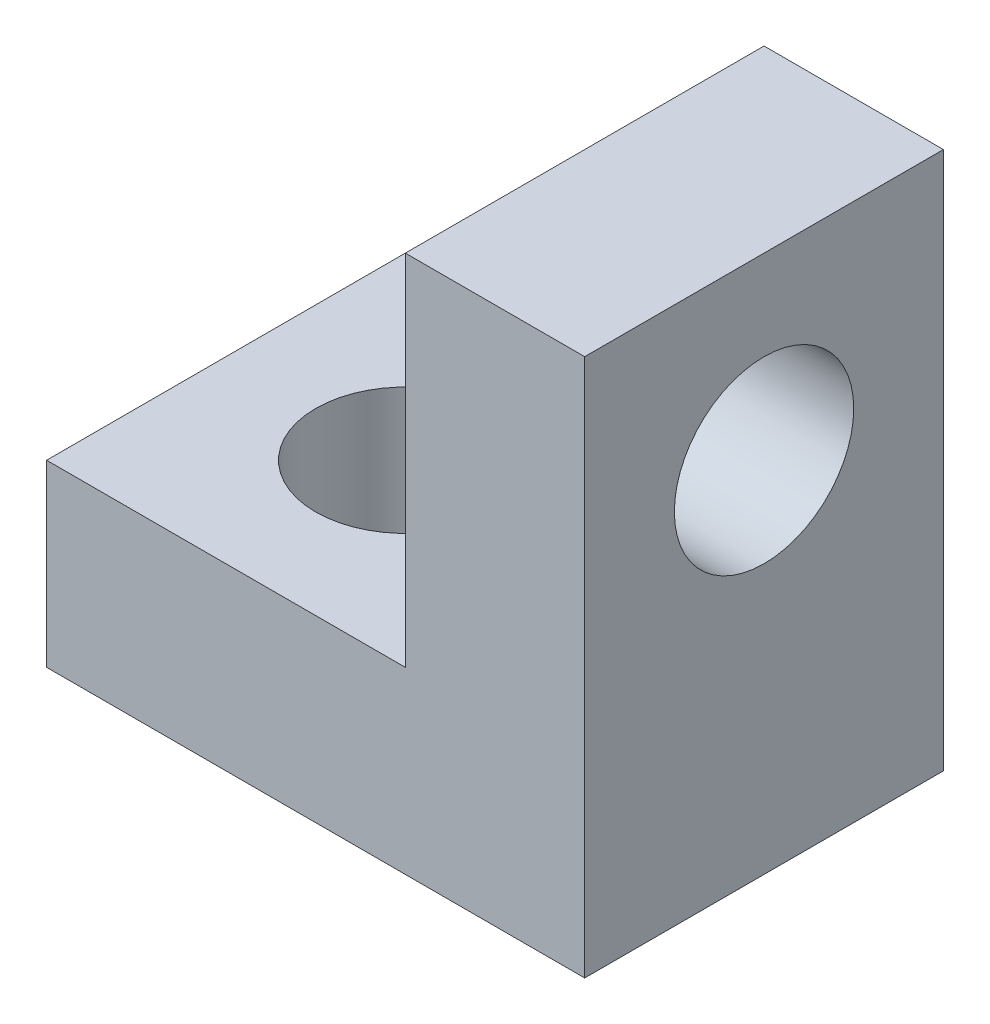
SolidWorks part; units mm, degrees
ref_plane "Front Plane" through (0, 0, 0) normal (0, 0, 1) x (1, 0, 0)
ref_plane "Top Plane" through (0, 0, 0) normal (0, 1, 0) x (1, 0, 0)
ref_plane "Right Plane" through (0, 0, 0) normal (1, 0, 0) x (0, 0, -1)
sketch3d "3DSketch1"
  line L0 (0, 0, 0) -> (10, 0, 0)
  line L1 (10, 0, 0) -> (10, 10, 0)
  line L2 (10, 10, 0) -> (15, 10, 0)
  line L3 (15, 10, 0) -> (15, -5, 0)
  line L4 (15, -5, 0) -> (0, -5, 0)
  line L5 (0, -5, 0) -> (0, 0, 0)
  dimension "D1" = 5
  dimension "D2" = 5
  dimension "D3" = 10
  dimension "D4" = 15
ref_plane "Plane1" through (15, -5, 0) normal (0, -1, 0) x (-1, 0, 0)
extrude "Boss-Extrude1" add sketch "3DSketch1" along direction (0, 0, 1) on the side against the normal blind 10
sketch "Sketch4" plane through (10, 0, 0) normal (-1, 0, 0) x (0, 0, 1)
  line L0 (10, 0) -> (10, 10) construction
  line L2 (0, 10) -> (10, 10) construction
  circle A0 centre (5, 5) radius 2.5
  point P6 (-1.1246, 11.1113)
  point P7 (5, 10)
  dimension "D1" = 5
  dimension "D2" = 5
  dimension "D3" = 5
extrude "Cut-Extrude1" cut sketch "Sketch4" against normal blind 5
sketch "Sketch5" plane through (0, 0, 0) normal (0, 1, 0) x (1, 0, 0)
  line L0 (0, 0) -> (10, 0) construction
  line L1 (0, 0) -> (0, -10) construction
  circle A0 centre (5, -5) radius 2.5
  dimension "D1" = 5
  dimension "D2" = 5
  dimension "D3" = 5
extrude "Cut-Extrude2" cut sketch "Sketch5" against normal blind 5
